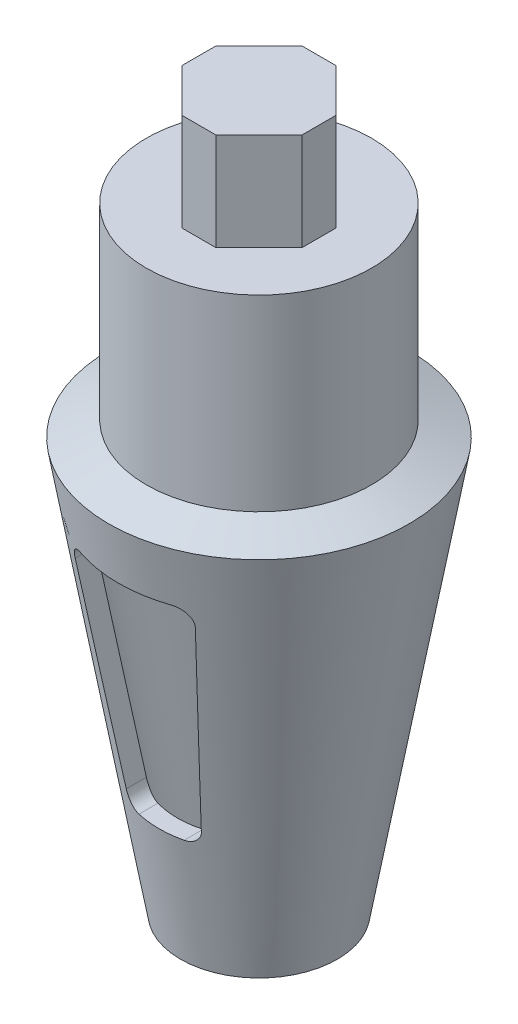
SolidWorks part; units mm, degrees
ref_plane "Front Plane" through (0, 0, 0) normal (0, 0, 1) x (1, 0, 0)
ref_plane "Top Plane" through (0, 0, 0) normal (0, 1, 0) x (1, 0, 0)
ref_plane "Right Plane" through (0, 0, 0) normal (1, 0, 0) x (0, 0, -1)
sketch "Sketch1" plane through (0, 0, 0) normal (0, 0, 1) x (1, 0, 0)
  line L0 (0, 95.7224) -> (0, 0) construction
  line L1 (0, 0) -> (30, 0)
  line L2 (30, 0) -> (30, -50)
  line L3 (30, -50) -> (40, -54)
  line L4 (40, -54) -> (20.8947, -164)
  line L5 (20.8947, -164) -> (16, -164)
  line L6 (16, -164) -> (31.6678, -73.7915)
  line L7 (27.9846, -67.1939) -> (20, -64)
  line L8 (20, -64) -> (20, -8)
  line L9 (20, -8) -> (0, -8)
  line L10 (0, -8) -> (0, 0)
  arc A0 (31.6678, -73.7915) -> (27.9846, -67.1939) centre (25.7563, -72.7647) ccw
  point P10 (30, -25)
  point P14 (20, -36)
  point P22 (32.5, -69)
  dimension "D11" = 6
  dimension "D1" = 30
  dimension "D2" = 20
  dimension "D3" = 4
  dimension "D4" = 16
  dimension "D5" = 110
  dimension "D6" = 40
  dimension "D7" = 8
  dimension "D8" = 50
  dimension "D9" = 56
  dimension "D10" = 5
revolve "Revolve1" add sketch "Sketch1" angle 360 about L0
sketch "Sketch2" plane through (0, 0, 0) normal (0, 1, 0) x (1, 0, 0)
  line L0 (0, 40) -> (0, 20.5493) construction
  line L1 (-40, 0) -> (-20.5493, 0) construction
  line L2 (4.5061, 16) -> (16, 4.5061)
  line L3 (-4.5061, 16) -> (-16, 4.5061)
  line L4 (16, -4.5061) -> (4.5061, -16)
  line L5 (-16, -4.5061) -> (-4.5061, -16)
  line L6 (-4.5061, 16) -> (4.5061, 16)
  line L7 (-4.5061, -16) -> (4.5061, -16)
  line L8 (16, 4.5061) -> (16, -4.5061)
  line L9 (-16, 4.5061) -> (-16, -4.5061)
  line L10 (0, 16) -> (0, -40) construction
  line L11 (-16, 0) -> (40, 0) construction
  circle A0 centre (0, 0) radius 40 construction
  point P19 (0, 19.2338)
  point P20 (20.5493, 0)
  dimension "D1" = 32
  dimension "D2" = 32
  dimension "D3" = 29
extrude "Boss-Extrude1" add sketch "Sketch2" along normal blind 26
sketch "Sketch3" plane through (0, 0, 0) normal (0, 0, 1) x (1, 0, 0)
  line L0 (0, 26) -> (0, -164) construction
  line L1 (-4.5061, 26) -> (4.5061, 26) construction
  line L2 (-20.8947, -164) -> (20.8947, -164) construction
  line L3 (-12.0245, -69) -> (12.0245, -69)
  line L4 (16, -73.4417) -> (10, -127.4417)
  line L5 (6.0245, -131) -> (-6.0245, -131)
  line L6 (-16, -73.4417) -> (-10, -127.4417)
  arc A0 (-10, -127.4417) -> (-6.0245, -131) centre (-6.0245, -127) ccw
  arc A1 (10, -127.4417) -> (6.0245, -131) centre (6.0245, -127) cw
  arc A2 (-16, -73.4417) -> (-12.0245, -69) centre (-12.0245, -73) cw
  arc A3 (12.0245, -69) -> (16, -73.4417) centre (12.0245, -73) cw
  point P11 (0, -131)
  point P12 (0, -69)
  point P14 (-9.6046, -131)
  point P17 (9.6046, -131)
  point P20 (-16.4935, -69)
  point P23 (16.4935, -69)
  dimension "D4" = 4
  dimension "D1" = 16
  dimension "D2" = 10
  dimension "D3" = 62
extrude "Cut-Extrude1" cut sketch "Sketch3" against normal through all both and the other way through all contours L5 A0 L6 A2 L3 A3 L4 A1
